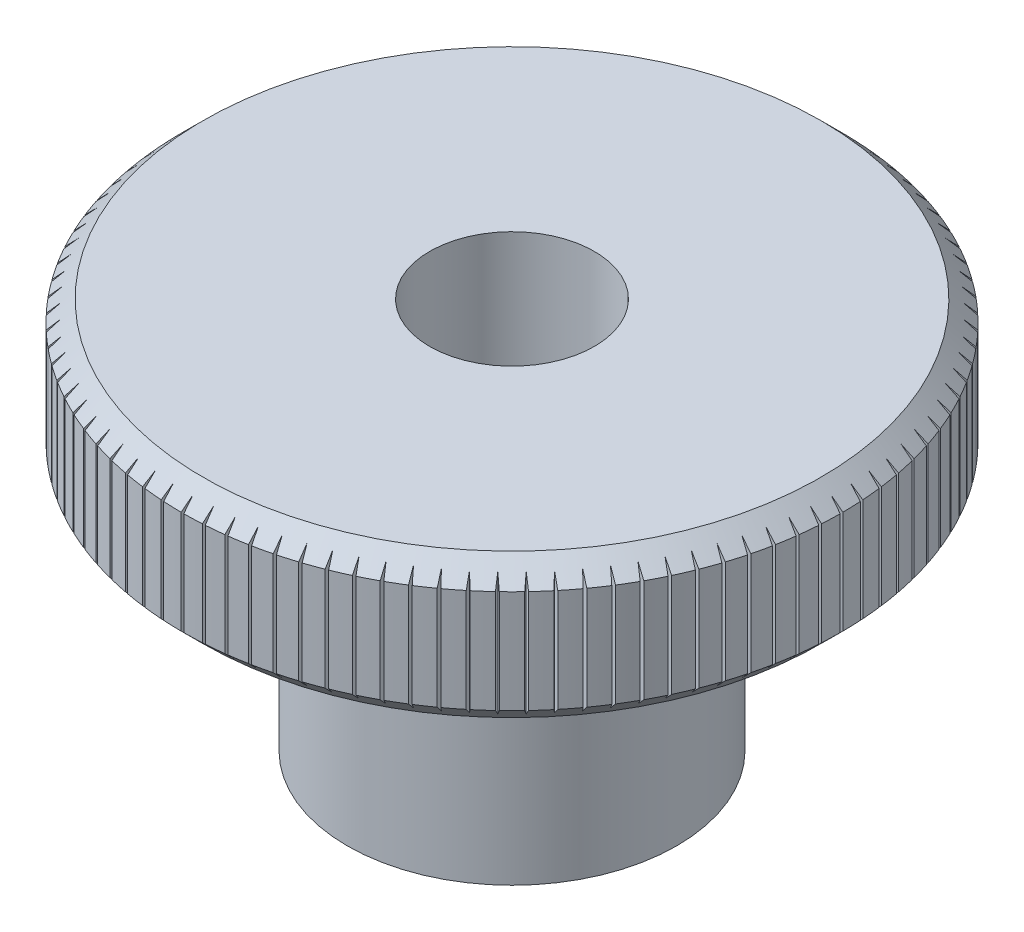
SolidWorks part; units mm, degrees
ref_plane "Front Plane" through (0, 0, 0) normal (0, 0, 1) x (1, 0, 0)
ref_plane "Top Plane" through (0, 0, 0) normal (0, 1, 0) x (1, 0, 0)
ref_plane "Right Plane" through (0, 0, 0) normal (1, 0, 0) x (0, 0, -1)
sketch "Sketch1" plane through (0, 0, 0) normal (0, 0, 1) x (1, 0, 0)
  line L0 (0, 0) -> (0, -3885.4477) construction
  line L1 (2, 0) -> (2, 9.5)
  line L2 (2, 9.5) -> (8, 9.5)
  line L3 (8, 9.5) -> (8, 6)
  line L4 (8, 6) -> (4, 6)
  line L5 (4, 6) -> (4, 0)
  line L6 (4, 0) -> (2, 0)
  dimension "INNER DIAM" = 4
  dimension "HEAD DIAM" = 16
  dimension "BOSS DIAM" = 8
  dimension "HEIGHT" = 9.5
  dimension "KNURLED HEIGHT" = 3.5
revolve "Revolve1" add sketch "Sketch1" angle 360 about L0
fillet "Fillet1" radius 0.8 1 edges at (0, 6, 4)
chamfer "Chamfer1" distance 0.5 angle 45 2 edges at (0, 6, 8) (0, 9.5, 8)
sketch "Sketch2" plane through (0, 9.5, 0) normal (0, 1, 0) x (1, 0, 0)
  line L0 (0.0329, 8) -> (-0.0329, 8)
  line L1 (-0.0329, 8) -> (0, 7.75)
  line L2 (0, 7.75) -> (0.0329, 8)
  circle A1 centre (0, 0) radius 8 construction
  point P0 (0, 8)
  point P3 (0, 8)
  dimension "D1" = 0.25
  dimension "D2" = 15
extrude "Cut-Extrude1" cut sketch "Sketch2" against normal through all
pattern_circular "CirPattern1" count 100 over 360 about axis through (0, 0, 0) along (0, 1, 0) of "Cut-Extrude1"
equation "\"D1@Fillet1\"= \"INNER DIAM@Sketch1\" / 5"
equation "\"D1@Chamfer1\" = \"INNER DIAM@Sketch1\" / 8"
equation "\"D1@Sketch2\"= \"D1@Chamfer1\" / 2"
